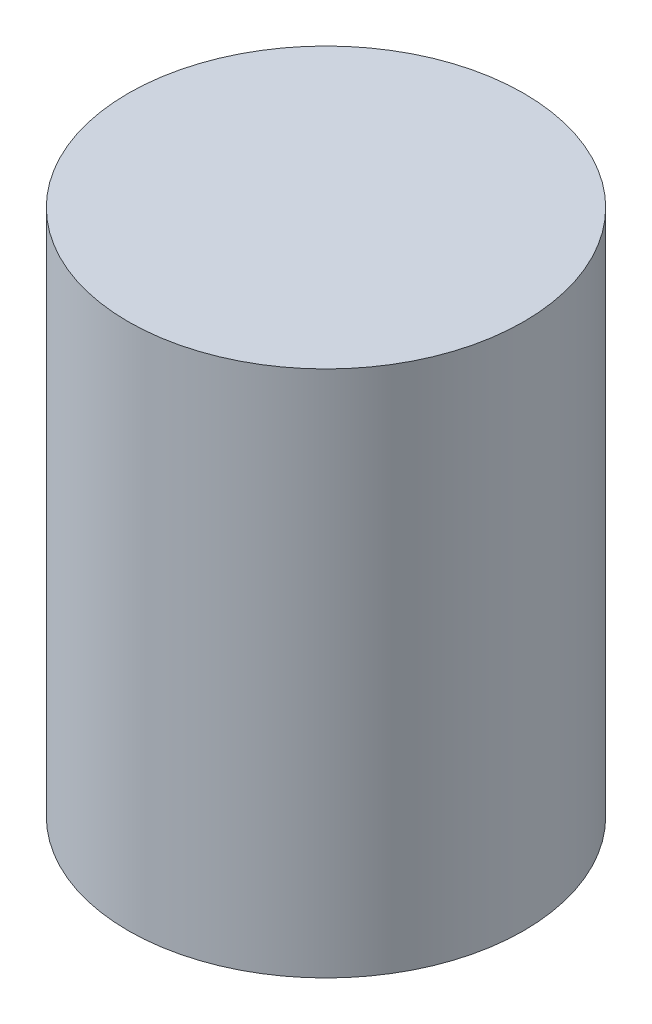
SolidWorks part; units mm, degrees
ref_plane "Front" through (0, 0, 0) normal (0, 0, 1) x (1, 0, 0)
ref_plane "Top" through (0, 0, 0) normal (0, 1, 0) x (1, 0, 0)
ref_plane "Right" through (0, 0, 0) normal (1, 0, 0) x (0, 0, -1)
sketch "Sketch1" plane through (0, 152.4, 0) normal (0, 1, 0) x (1, 0, 0)
  circle A0 centre (0, 0) radius 57.15
  dimension "D1" = 114.3
extrude "Extrude1" add sketch "Sketch1" along normal blind 152.4
